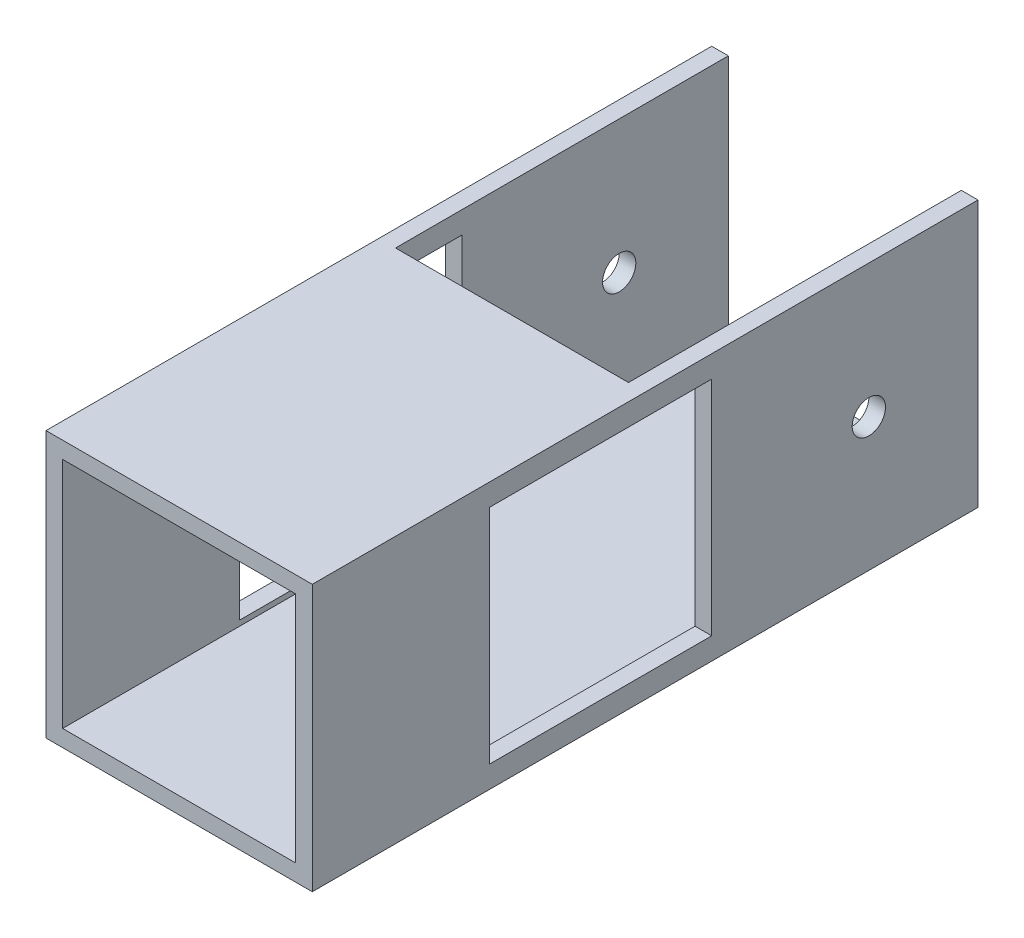
SolidWorks part; units mm, degrees
ref_plane "Front Plane" through (0, 0, 0) normal (0, 0, 1) x (1, 0, 0)
ref_plane "Top Plane" through (0, 0, 0) normal (0, 1, 0) x (1, 0, 0)
ref_plane "Right Plane" through (0, 0, 0) normal (1, 0, 0) x (0, 0, -1)
sketch "Sketch2" plane through (0, 0, 0) normal (0, 0, 1) x (1, 0, 0)
  line L1 (-25.4, 25.4) -> (25.4, 25.4)
  line L2 (-25.4, 25.4) -> (-25.4, -25.4)
  line L3 (-25.4, -25.4) -> (25.4, -25.4)
  line L4 (25.4, 25.4) -> (25.4, -25.4)
  line L5 (-25.4, 25.4) -> (25.4, -25.4) construction
  line L6 (-25.4, -25.4) -> (25.4, 25.4) construction
  line L7 (-22.225, 22.225) -> (22.225, 22.225)
  line L8 (-22.225, 22.225) -> (-22.225, -22.225)
  line L9 (-22.225, -22.225) -> (22.225, -22.225)
  line L10 (22.225, 22.225) -> (22.225, -22.225)
  line L11 (-22.225, 22.225) -> (22.225, -22.225) construction
  line L12 (-22.225, -22.225) -> (22.225, 22.225) construction
  point P0 (0, 0)
  point P6 (0, 0)
  dimension "D1" = 50.8
  dimension "D2" = 50.8
  dimension "D3" = 44.45
  dimension "D4" = 44.45
extrude "Boss-Extrude1" add sketch "Sketch2" along normal blind 127
sketch "Sketch4" plane through (0, 25.4, 0) normal (0, 1, 0) x (1, 0, 0)
  line L0 (25.4, 0) -> (-25.4, 0) construction
  line L1 (-22.225, 0) -> (22.225, 0)
  line L2 (-22.225, 0) -> (-22.225, -63.5)
  line L3 (-22.225, -63.5) -> (22.225, -63.5)
  line L4 (22.225, 0) -> (22.225, -63.5)
  line L5 (25.4, -127) -> (25.4, 0) construction
  line L6 (-25.4, -127) -> (-25.4, 0) construction
  dimension "D1" = 3.175
  dimension "D2" = 3.175
  dimension "D3" = 63.5
extrude "Cut-Extrude1" cut sketch "Sketch4" against normal blind 23.368
sketch "Sketch5" plane through (-25.4, 0, 0) normal (-1, 0, 0) x (0, 0, 1)
  line L0 (152.4, 0) -> (-49847.6, 0) construction
  line L1 (127, -25.4) -> (127, 25.4) construction
  line L2 (0, -25.4) -> (0, 25.4) construction
  line L3 (93.218, -21.209) -> (50.8, -21.209)
  line L4 (93.218, -21.209) -> (93.218, 21.209)
  line L5 (93.218, 21.209) -> (50.8, 21.209)
  line L6 (50.8, -21.209) -> (50.8, 21.209)
  line L7 (93.218, -21.209) -> (50.8, 21.209) construction
  line L8 (93.218, 21.209) -> (50.8, -21.209) construction
  circle A0 centre (20.828, 0) radius 3.175
  point P7 (127, 0)
  point P8 (72.009, 0)
  dimension "D1" = 6.35
  dimension "D2" = 0
  dimension "D3" = 20.828
  dimension "D4" = 42.418
  dimension "D5" = 42.418
  dimension "D6" = 50.8
extrude "Cut-Extrude2" cut sketch "Sketch5" against normal blind 100.1308
